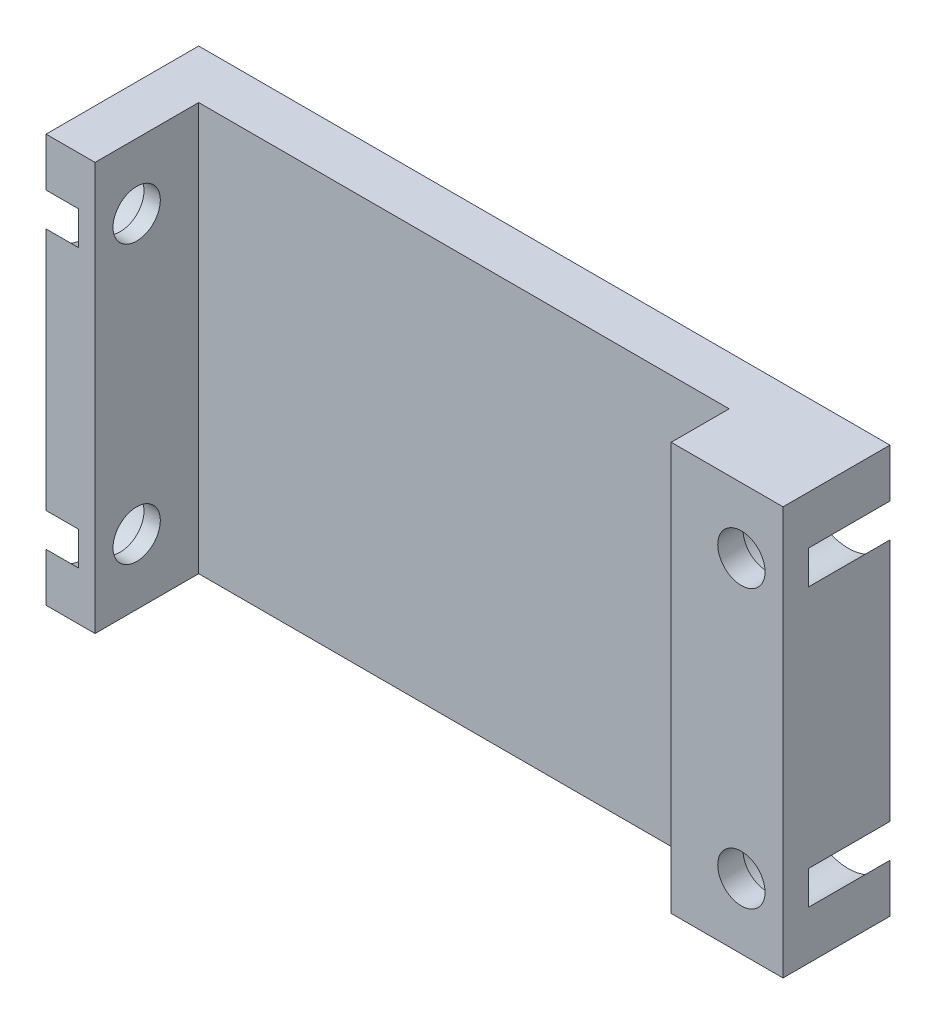
SolidWorks part; units mm, degrees
ref_plane "Plano frontal" through (0, 0, 0) normal (0, 0, 1) x (1, 0, 0)
ref_plane "Plano superior" through (0, 0, 0) normal (0, 1, 0) x (1, 0, 0)
ref_plane "Plano direito" through (0, 0, 0) normal (1, 0, 0) x (0, 0, -1)
sketch "Esboço2" plane through (0, 0, 0) normal (0, 0, 1) x (1, 0, 0)
  line L0 (0, 0) -> (0, -38.6) construction
  line L1 (-1.5, -22.5) -> (5.3501, -22.5)
  line L2 (-1.5, -22.5) -> (-1.5, 2.5)
  line L3 (-1.5, 2.5) -> (5.3501, 2.5)
  line L4 (5.3501, -22.5) -> (5.3501, 2.5)
  line L5 (2.8, -1.5) -> (2.8, 2.5) construction
  line L6 (2.8, -18.5) -> (2.8, -22.5) construction
  dimension "D1" = 0.25
  dimension "D2" = 4
  dimension "D3" = 1.5
extrude "Ressalto-extrusão2" add sketch "Esboço2" against normal offset from surface (3.55 mm away) 1 from offset 0.25 offset against normal yes
sketch "Esboço3" plane through (0, 0, -3.8) normal (0, 0, -1) x (-1, 0, 0)
  line L0 (33.75, 0) -> (33.75, -38.6) construction
  line L1 (-5.3501, 2.5) -> (34, 2.5)
  line L2 (-5.3501, 2.5) -> (-5.3501, -22.5)
  line L3 (-5.3501, -22.5) -> (34, -22.5)
  line L4 (34, 2.5) -> (34, -22.5)
  line L5 (-5.3501, -22.5) -> (1.5, -22.5) construction
  dimension "D1" = 0.25
extrude "Ressalto-extrusão3" add sketch "Esboço3" along normal blind 3
sketch "Esboço4" plane through (-34, 0, 0) normal (-1, 0, 0) x (0, 0, 1)
  line L1 (-6.8, -22.5) -> (2.55, -22.5)
  line L2 (-6.8, -22.5) -> (-6.8, 2.5)
  line L3 (-6.8, 2.5) -> (2.55, 2.5)
  line L4 (2.55, -22.5) -> (2.55, 2.5)
  line L5 (-6.8, 2.5) -> (-3.8, 2.5) construction
  dimension "D1" = 0.25
extrude "Ressalto-extrusão4" add sketch "Esboço4" along normal blind 3
hole_wizard "CBORE for M2.5 SHCS2" positions "3DSketch1" profile "Sketch1" counterbore size "M2.5" standard "ANSI Metric"
sketch3d "3DSketch1"
  circle A0 centre (-33.75, -1.5, 0) radius 1.35 construction
  circle A1 centre (-33.75, -18.5, 0) radius 1.35 construction
  point P0 (-37, -1.5, 0)
  point P7 (-32.4, -1.5, 0)
  point P8 (-37, -18.5, 0)
  point P20 (-32.4, -18.5, 0)
sketch "Sketch1" plane through (-37, -1.5, 0) normal (0, 1, 0) x (0, 0, 1)
  line L0 (0, 0) -> (0, 3.8712)
  line L1 (0, 3.8712) -> (1.45, 3)
  line L2 (1.45, 3) -> (1.45, 2)
  line L3 (1.45, 2) -> (2.75, 2)
  line L4 (2.75, 2) -> (2.75, 0)
  line L5 (2.75, 0) -> (0, 0)
  line L10 (0, 3.8712) -> (-1.45, 3) construction
  line L11 (0, -6.35) -> (0, 107.95) construction
  dimension "Hole Dia." = 2.9
  dimension "Hole Depth" = 3
  dimension "C'Bore Dia." = 5.5
  dimension "C'Bore Depth" = 2
  dimension "Drill Angle" = 118
hole_wizard "CBORE for M2.5 SHCS3" positions "Sketch2" profile "Sketch4" counterbore size "M2.5" standard "ANSI Metric" end condition up to next
sketch "Sketch2" plane through (0, 0, -6.8) normal (0, 0, -1) x (-1, 0, 0)
  circle A0 centre (-2.8, -1.5) radius 1.35 construction
  point P0 (-2.8, -1.5)
  point P6 (-2.8, -18.5)
sketch "Sketch4" plane through (2.8, -1.5, -6.8) normal (1, 0, 0) x (0, 1, 0)
  line L0 (0, 0) -> (0, 6.55)
  line L1 (0, 6.55) -> (1.45, 6.55)
  line L3 (1.45, 6.55) -> (1.45, 5)
  line L4 (1.45, 5) -> (2.75, 5)
  line L5 (2.75, 5) -> (2.75, 0)
  line L7 (2.75, 0) -> (0, 0)
  line L11 (0, -6.35) -> (0, 107.95) construction
  dimension "Thru Hole Dia." = 2.9
  dimension "Thru Hole Depth" = 6.55
  dimension "C'Bore Dia." = 5.5
  dimension "C'Bore Depth" = 5
move or copy body "Corpo-Mover/Copiar1" [suppressed] bodies to move or copy 104
